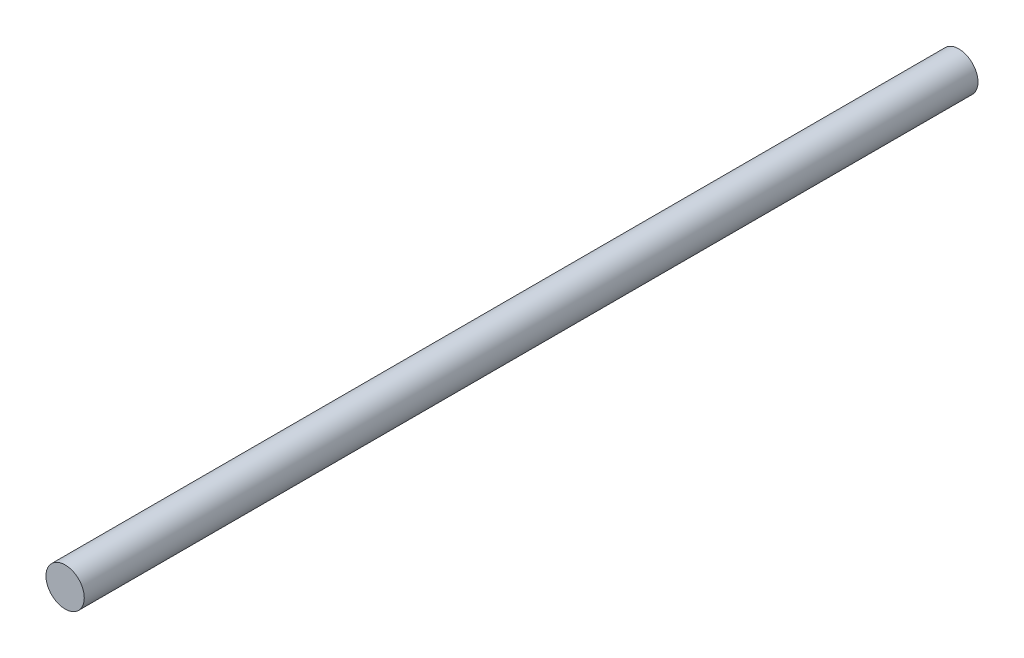
SolidWorks part; units mm, degrees
material "1023 Carbon Steel Sheet (SS)"
ref_plane "Front" through (0, 0, 0) normal (0, 0, 1) x (1, 0, 0)
ref_plane "Top" through (0, 0, 0) normal (0, 1, 0) x (1, 0, 0)
ref_plane "Right" through (0, 0, 0) normal (1, 0, 0) x (0, 0, -1)
sketch "Sketch1" plane through (0, 0, 0) normal (0, 0, 1) x (1, 0, 0)
  circle A0 centre (0, 0) radius 1.5
  dimension "D1" = 3
extrude "Boss-Extrude1" add sketch "Sketch1" along normal blind 70
